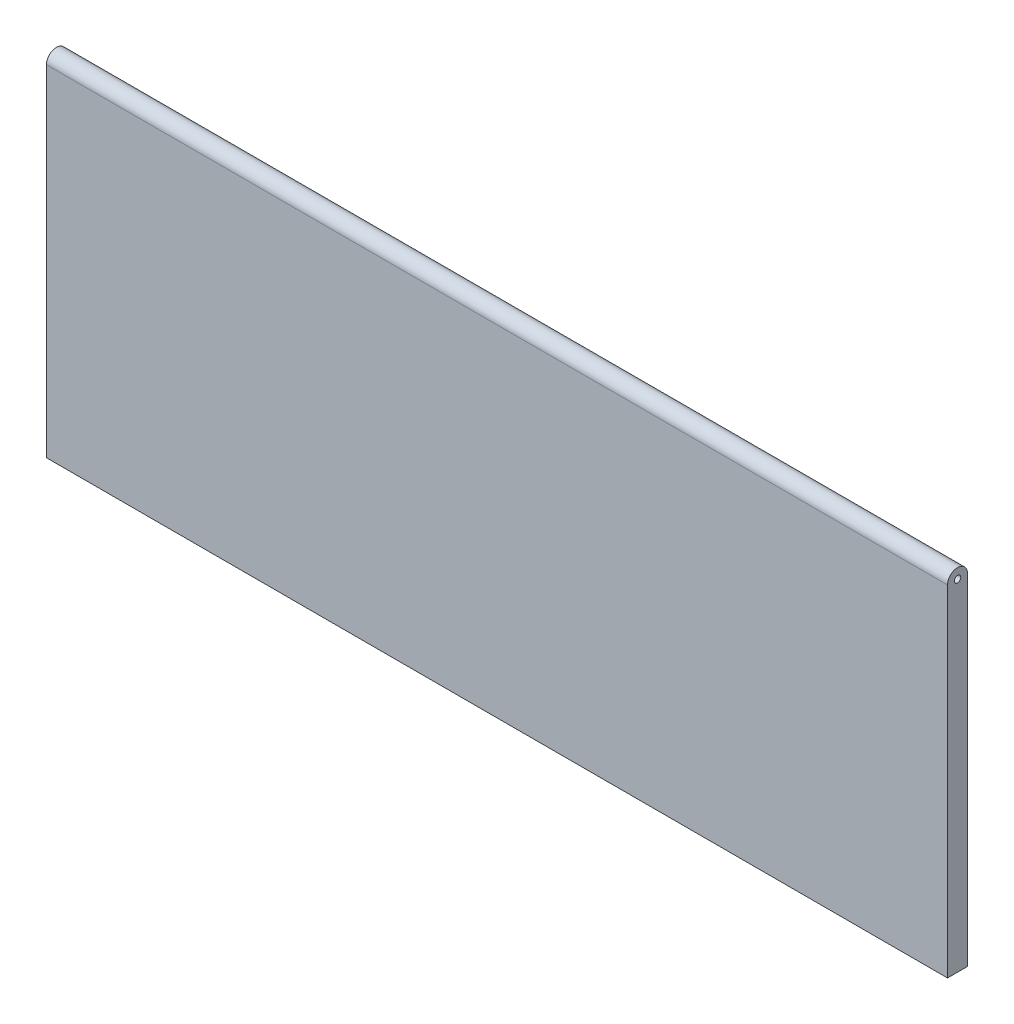
SolidWorks part; units mm, degrees
ref_plane "Front Plane" through (0, 0, 0) normal (0, 0, 1) x (1, 0, 0)
ref_plane "Top Plane" through (0, 0, 0) normal (0, 1, 0) x (1, 0, 0)
ref_plane "Right Plane" through (0, 0, 0) normal (1, 0, 0) x (0, 0, -1)
sketch "Sketch5" plane through (0, 0, 0) normal (1, 0, 0) x (0, 0, -1)
  line L0 (0, 44.45) -> (0, 41.91) construction
  line L1 (-2.54, -44.45) -> (2.54, -44.45)
  line L2 (-2.54, -44.45) -> (-2.54, 41.91)
  line L4 (2.54, -44.45) -> (2.54, 41.91)
  line L5 (-2.54, -44.45) -> (2.436, 42.6295) construction
  line L6 (-2.436, 42.6295) -> (2.54, -44.45) construction
  arc A0 (-2.54, 41.91) -> (2.54, 41.91) centre (0, 41.91) cw
  circle A1 centre (0, 41.91) radius 0.8255
  point P0 (0, 0)
  dimension "D1" = 1.651
  dimension "D2" = 2.54
extrude "Boss-Extrude2" add sketch "Sketch5" along normal blind 228.6
